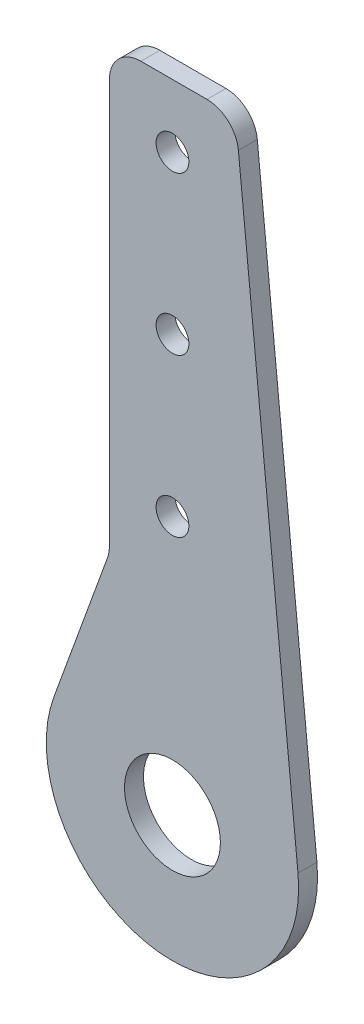
SolidWorks part; units mm, degrees
ref_plane "正面" through (0, 0, 0) normal (0, 0, 1) x (1, 0, 0)
ref_plane "平面" through (0, 0, 0) normal (0, 1, 0) x (1, 0, 0)
ref_plane "右側面" through (0, 0, 0) normal (1, 0, 0) x (0, 0, -1)
sketch "ｽｹｯﾁ2" plane through (0, 0, 0) normal (0, 0, 1) x (1, 0, 0)
  line L0 (10.6066, 10.6066) -> (-10.6066, -10.6066) construction
  line L1 (10.6066, -10.6066) -> (-10.6066, 10.6066) construction
  line L2 (0, 0) -> (10, 66) construction
  line L3 (0, 41) -> (0, 66) construction
  line L4 (0, 66) -> (0, 91) construction
  line L5 (-10, 101) -> (-10, 31)
  line L6 (-10, 31) -> (10, 31) construction
  line L7 (-10, 101) -> (10, 101)
  line L8 (10, 101) -> (10, 31) construction
  line L9 (10, 101) -> (19.9007, 1.99)
  line L11 (-10, 66) -> (10, 66) construction
  line L12 (-10, 31) -> (-18.7937, 6.8407)
  line L13 (-10, -24) -> (-10, 31) construction
  line L15 (0, -24) -> (-10, -24) construction
  line L16 (-10, -24) -> (-10, 31) construction
  circle A0 centre (0, 0) radius 7.6
  circle A1 centre (-10.6066, 10.6066) radius 1.6 construction
  circle A2 centre (10.6066, 10.6066) radius 1.6 construction
  circle A3 centre (10.6066, -10.6066) radius 1.6 construction
  circle A4 centre (-10.6066, -10.6066) radius 1.6 construction
  circle A5 centre (0, 66) radius 2.6
  circle A6 centre (0, 91) radius 2.6
  circle A7 centre (0, 41) radius 2.6
  arc A8 (-18.7937, 6.8407) -> (19.9007, 1.99) centre (0, 0) ccw
  circle A9 centre (0, 0) radius 76 construction
  circle A10 centre (0, 0) radius 24 construction
  point P6 (0, 0)
  point P9 (0, 0)
  point P29 (0, 66)
  dimension "D1" = 15.2
  dimension "D2" = 3.2
  dimension "D3" = 5.2
  dimension "D4" = 25
  dimension "D5" = 25
  dimension "D8" = 20
  dimension "D9" = 20
  dimension "D11" = 10
  dimension "D12" = 152
  dimension "D13" = 10
  dimension "D15" = 48
  dimension "D14" = 55
  dimension "D6" = 45
  dimension "D7" = 30
  dimension "D10" = 10
extrude "ﾎﾞｽ - 押し出し1" add sketch "ｽｹｯﾁ2" along normal blind 3
fillet "ﾌｨﾚｯﾄ7" radius 5 3 edges at (-10, 31, 1.5) (10, 101, 1.5) (-10, 101, 1.5)
